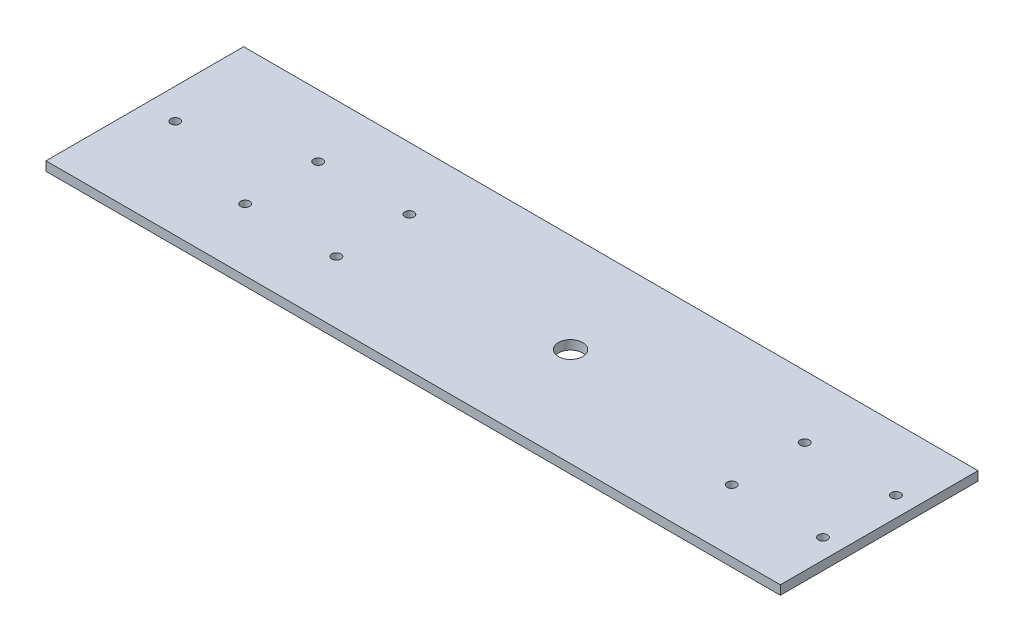
SolidWorks part; units mm, degrees
ref_plane "Front Plane" through (0, 0, 0) normal (0, 0, 1) x (1, 0, 0)
ref_plane "Top Plane" through (0, 0, 0) normal (0, 1, 0) x (1, 0, 0)
ref_plane "Right Plane" through (0, 0, 0) normal (1, 0, 0) x (0, 0, -1)
sketch "Sketch1" plane through (0, 0, 0) normal (0, 1, 0) x (1, 0, 0)
  line L0 (-140, 0) -> (101.5, 0) construction
  line L1 (-140, -32.5) -> (101.5, -32.5)
  line L2 (-140, -32.5) -> (-140, 32.5)
  line L3 (-140, 32.5) -> (101.5, 32.5)
  line L4 (101.5, -32.5) -> (101.5, 32.5)
  dimension "D1" = 101.5
  dimension "D2" = 65
  dimension "D3" = 140
extrude "Boss-Extrude1" add sketch "Sketch1" along normal mid plane 3
sketch "Sketch3" plane through (0, 1.5, 0) normal (0, 1, 0) x (1, 0, 0)
  line L0 (-140, 0) -> (101.5, 0) construction
  line L1 (-140, 32.5) -> (-140, -32.5) construction
  line L2 (101.5, -32.5) -> (101.5, 32.5) construction
  circle A0 centre (0, 0) radius 4
  dimension "D2" = 8
extrude "Cut-Extrude2" cut sketch "Sketch3" against normal through all
sketch "Sketch4" plane through (0, 1.5, 0) normal (0, 1, 0) x (1, 0, 0)
  line L0 (101.5, 0) -> (0, 0) construction
  line L1 (101.5, -32.5) -> (101.5, 32.5) construction
  line L2 (65, 12) -> (101.5, 12) construction
  line L3 (65, -12) -> (95, -12) construction
  line L4 (80, -12) -> (80, 12) construction
  circle A0 centre (65, 12) radius 1.5
  circle A1 centre (95, 12) radius 1.5
  circle A2 centre (95, -12) radius 1.5
  circle A3 centre (65, -12) radius 1.5
  circle A5 centre (0, 0) radius 4 construction
  dimension "D1" = 3
  dimension "D2" = 3
  dimension "D3" = 30
  dimension "D4" = 80
  dimension "D5" = 24
extrude "Cut-Extrude3" cut sketch "Sketch4" against normal through all both and the other way through all
mirror "Mirror2" about plane through (0, 0, 0) normal (1, 0, 0) of "Cut-Extrude3"
sketch "Sketch5" plane through (0, 1.5, 0) normal (0, 1, 0) x (1, 0, 0)
  line L1 (-140, 0) -> (101.5, 0) construction
  line L2 (-140, 32.5) -> (-140, -32.5) construction
  line L3 (101.5, -32.5) -> (101.5, 32.5) construction
  circle A2 centre (-130, 0) radius 1.5
  dimension "D1" = 3
  dimension "D2" = 10
extrude "Cut-Extrude4" cut sketch "Sketch5" against normal through all both and the other way through all
